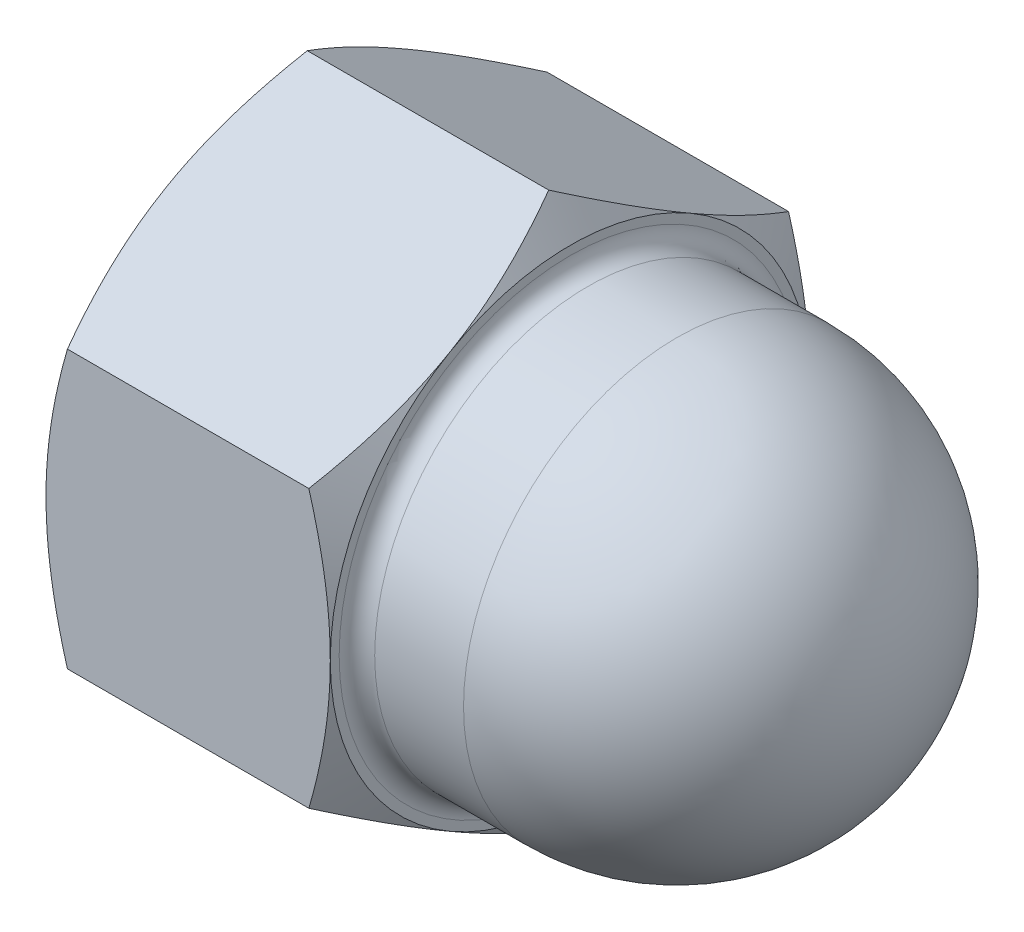
SolidWorks part; units mm, degrees
extrude "BaseNut" add sketch "BaseNutSke" along normal blind 16
sketch "BaseNutSke" plane through (0, 0, 0) normal (1, 0, 0) x (0, 0, -1)
  line L6 (13.5, 7.7942) -> (13.5, -7.7942)
  line L7 (-13.5, 7.7942) -> (-13.5, -7.7942)
  line L8 (13.5, 7.7942) -> (0, 15.5885)
  line L9 (0, 15.5885) -> (-13.5, 7.7942)
  line L10 (-13.5, -7.7942) -> (0, -15.5885)
  line L11 (0, -15.5885) -> (13.5, -7.7942)
  dimension "D4" = 60
  dimension "D1" = 120
  dimension "D2" = 13.5
  dimension "D3" = 13.5
  dimension "Width_flats" = 27
revolve "DoubleChamfer" cut sketch "Sketch4" angle 360 about L10
sketch "Sketch4" plane through (0, 0, 0) normal (0, 0, 1) x (1, 0, 0)
  line L0 (0, 13.5) -> (2.5048, 17.8385)
  line L1 (16, 13.5) -> (13.4952, 17.8385)
  line L2 (2.5048, 17.8385) -> (13.4952, 17.8385)
  line L3 (16, 13.5) -> (18, 13.5)
  line L4 (18, 13.5) -> (18, 28.5)
  line L5 (18, 28.5) -> (-2, 28.5)
  line L6 (0, 13.5) -> (-2, 13.5)
  line L7 (-2, 13.5) -> (-2, 28.5)
  line L8 (16, 15.5885) -> (16, 7.7942) construction
  line L9 (0, 15.5885) -> (0, 7.7942) construction
  line L10 (0, 0) -> (57.15, 0) construction
  line L11 (16, 15.5885) -> (0, 15.5885) construction
  point P17 (16, 13.5)
  dimension "D1" = 30
  dimension "D2" = 30
  dimension "D3" = 2
  dimension "D4" = 2
  dimension "D5" = 2.25
  dimension "D6" = 15
  dimension "D7" = 13.5
revolve "TapDrill" cut sketch "TapDriSke"
sketch "TapDriSke" plane through (0, 0, 0) normal (0, 0, 1) x (1, 0, 0)
  line L0 (0, 0) -> (44.45, 0) construction
  line L1 (0, 8.75) -> (27, 8.75)
  line L2 (0, 0) -> (0, -11.6913) construction
  line L3 (27, 8.75) -> (32.2575, 0)
  line L4 (0, 0) -> (63.5, 0) construction
  line L5 (32.2575, 0) -> (0, 0)
  line L6 (0, 0) -> (0, 8.75)
  line L7 (27, -8.75) -> (32.2575, 0) construction
  line L8 (0, -8.75) -> (27, -8.75) construction
  line L9 (0.5, 6.35) -> (0.5, 3.175) construction
  dimension "Drill_depth" = 27
cosmetic thread "ThreadCosmetic" [suppressed]
revolve "EndChamfer" cut sketch "EndChamferSketch" angle 360 about L4
sketch "EndChamferSketch" plane through (0, 0, 0) normal (0, 0, 1) x (1, 0, 0)
  line L0 (-0.0254, 10) -> (0.0254, 10)
  line L1 (0.0254, 10) -> (0.9882, 8.625)
  line L2 (0.9882, 8.625) -> (-0.0254, 8.625)
  line L3 (-0.0254, 8.625) -> (-0.0254, 10)
  line L4 (0, 0) -> (-15.875, 0) construction
  dimension "D1" = 0.0508
  dimension "D2" = 35
  dimension "D3" = 0.0254
  dimension "ChamferDepth" = 1.375
  dimension "ThreadMajor" = 10
ref_plane "Plane1" through (0, 0, 0) normal (0, 0, 1) x (1, 0, 0)
ref_plane "Plane2" through (0, 0, 0) normal (0, 1, 0) x (1, 0, 0)
ref_plane "Plane3" through (0, 0, 0) normal (1, 0, 0) x (0, 0, -1)
sketch "DomeSke" plane through (0, 0, 0) normal (0, 0, 1) x (1, 0, 0)
  line L0 (0, 0) -> (63.5, 0) construction
  line L1 (0, 7.7942) -> (0, -7.7942) construction
  line L2 (34, 0) -> (0, 0)
  line L3 (0, 12) -> (22, 12)
  line L4 (0, -12) -> (22.225, -12) construction
  line L5 (0, 12) -> (0, 0)
  arc A0 (22, 12) -> (34, 0) centre (22, 0) cw
revolve "Dome" add sketch "DomeSke" angle 360 about L0
sketch "GrvSke" plane through (0, 0, 0) normal (0, 0, 1) x (1, 0, 0)
  line L0 (0, 0) -> (38.1, 0) construction
  line L1 (16, 10.5) -> (16, 7.75)
  line L2 (16, 7.75) -> (23, 7.75)
  line L3 (23, 7.75) -> (23, 10.5)
  line L4 (23, 10.5) -> (16, 10.5)
  line L5 (16, 0) -> (16, 11.6913) construction
  line L6 (27, 8.75) -> (0, 8.75) construction
  dimension "D1" = 1
revolve "Groove" cut sketch "GrvSke" angle 360 about L0
sketch "ThdSchSke" plane through (0, 0, 0) normal (0, 1, 0) x (1, 0, 0)
  line L0 (0.0381, 10) -> (-0.8372, 8.75)
  line L1 (-0.8372, 8.75) -> (-0.8372, 4.375)
  line L2 (-0.8372, 4.375) -> (0.9134, 4.375)
  line L3 (0.9134, 4.375) -> (0.9134, 8.75)
  line L4 (0.9134, 8.75) -> (0.0381, 10)
  line L5 (-38.1, 0) -> (3.175, 0) construction
  line L6 (0, 0) -> (-15.875, 0) construction
  line L7 (0, 0) -> (63.5, 0) construction
  line L9 (2.5381, 0.475) -> (2.5381, -5.875) construction
  dimension "D1" = 0.0381
  dimension "Thread_major" = 20
  dimension "Tap_drill" = 17.5
  dimension "OverCut" = 8.75
revolve "ThreadSchematic" [suppressed] cut sketch "ThdSchSke" angle 360 about L5
pattern_linear "ThdSchPat" [suppressed]
fillet "DomeFillet" radius 1 1 edges at (16, 0, -12)
equation "' \"Width_flats@BaseNutSke\" = 27"
equation "' \"Hex_ht@BaseNut\" = 16"
equation "' \"Overall_ht@DomeSke\" = 34"
equation "' \"Dome_rad@DomeSke\" = 12"
equation "' \"Thread_min@TapDriSke\" = 17.5"
equation "' \"Drill_clr@TapDriSke\" = 1.0"
equation "' \"Advance@ThdSchSke\" = 2.5"
equation "' \"Thread_nominal@ThreadCosmetic\" = 20"
equation "' \"Radius@DomeFillet\" = 1.0"
equation "' \"Groove_wid@GrvSke\" = 7"
equation "\"Drill_depth@TapDriSke\" = \"Overall_ht@DomeSke\"  - \"Drill_clr@TapDriSke\" - 0.3 * \"Thread_nominal@ThreadCosmetic\""
equation "\"Groove_dia@GrvSke\" = \"Thread_nominal@ThreadCosmetic\" * 1.05"
equation "\"Thread_depth@ThreadCosmetic\" = \"Thread_nominal@ThreadCosmetic\""
equation "\"D2@BaseNutSke\" = \"Width_flats@BaseNutSke\" / 2"
equation "\"D3@BaseNutSke\" = \"Width_flats@BaseNutSke\" / 2"
equation "\"D7@Sketch4\" = \"Width_flats@BaseNutSke\" / 2"
equation "\"D5@Sketch4\" = \"Width_flats@BaseNutSke\" / 12"
equation "\"Thread_major@ThdSchSke\" = \"Thread_nominal@ThreadCosmetic\""
equation "\"Tap_drill@ThdSchSke\" = \"Thread_min@TapDriSke\""
equation "\"OverCut@ThdSchSke\" = \"Tap_drill@ThdSchSke\" * 0.5"
equation "\"Num_threads@ThdSchPat\" = int(  ( \"Hex_ht@BaseNut\" - 0.002 ) / \"Advance@ThdSchSke\" + 0.999 )  + 1"
equation "' \"Num_threads@ThdSchPat\" = int(  ( \"Thread_depth@ThreadCosmetic\" - 0.002 ) / \"Advance@ThdSchSke\" + 0.999 )  + 1"
equation "\"Advance@ThdSchPat\" = ( \"Hex_ht@BaseNut\" - 0.002 ) /  (\"Num_threads@ThdSchPat\" - 1) 'relax it"
equation "' \"Advance@ThdSchPat\" = ( \"Thread_depth@ThreadCosmetic\" - 0.002 ) /  (\"Num_threads@ThdSchPat\" - 1) 'relax it"
equation "\"ThreadMajor@EndChamferSketch\" = \"Thread_nominal@ThreadCosmetic\" * 0.5"
equation "\"ChamferDepth@EndChamferSketch\" = (\"Thread_nominal@ThreadCosmetic\" - \"Thread_min@TapDriSke\") * 0.55"
